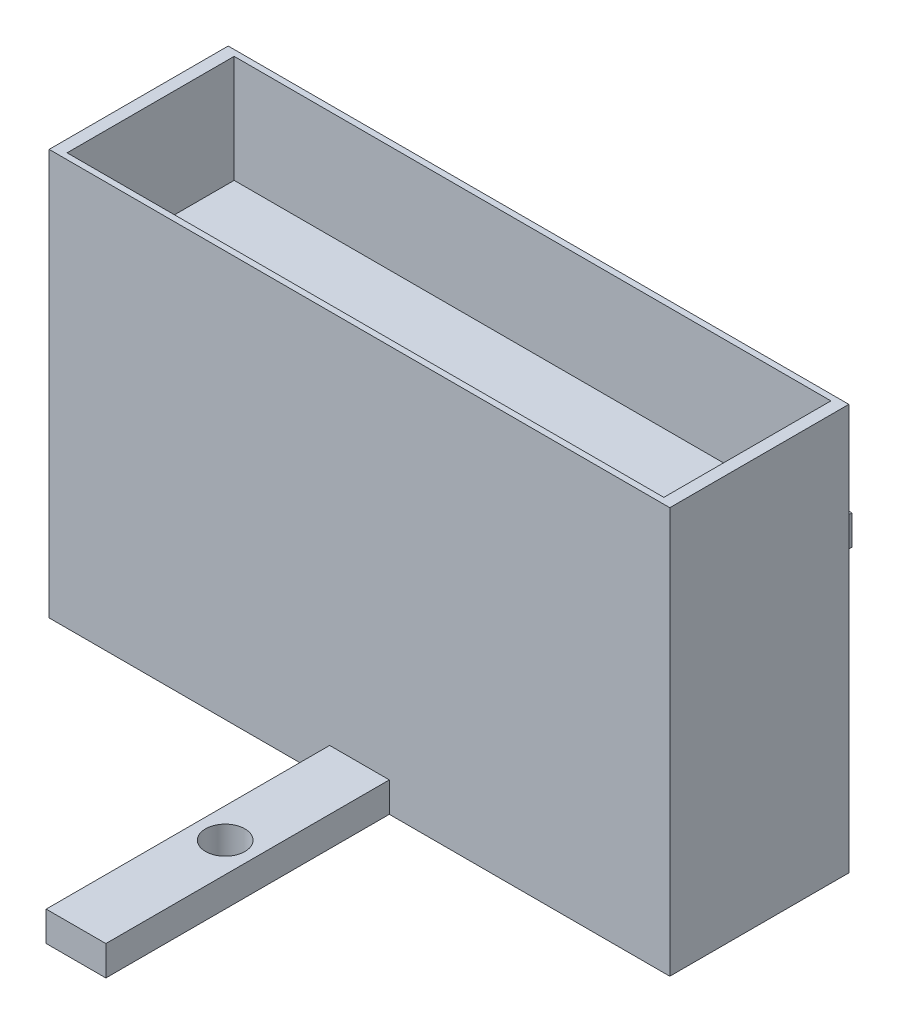
SolidWorks part; units mm, degrees
ref_plane "Front Plane" through (0, 0, 0) normal (0, 0, 1) x (1, 0, 0)
ref_plane "Top Plane" through (0, 0, 0) normal (0, 1, 0) x (1, 0, 0)
ref_plane "Right Plane" through (0, 0, 0) normal (1, 0, 0) x (0, 0, -1)
sketch "Sketch2" plane through (0, 0, 0) normal (0, 1, 0) x (1, 0, 0)
  line L1 (-52, -15) -> (52, -15)
  line L2 (-52, -15) -> (-52, 15)
  line L3 (-52, 15) -> (52, 15)
  line L4 (52, -15) -> (52, 15)
  line L5 (-52, -15) -> (52, 15) construction
  line L6 (-52, 15) -> (52, -15) construction
  point P0 (0, 0)
  point P6 (0, 0)
  point P7 (0, 0)
  point P8 (0, 0)
  point P9 (0, 0)
  point P10 (0, 0)
  point P11 (0, 0)
  point P12 (0, 0)
  point P13 (0, 0)
  point P14 (0, 0)
  point P15 (0, 0)
  point P16 (0, 0)
  point P17 (0, 0)
  point P18 (0, 0)
extrude "Boss-Extrude1" add sketch "Sketch2" along normal blind 68
sketch "Sketch3" plane through (0, 68, 0) normal (0, 1, 0) x (1, 0, 0)
  line L1 (-50, 14) -> (50, 14)
  line L2 (-50, 14) -> (-50, -14)
  line L3 (-50, -14) -> (50, -14)
  line L4 (50, 14) -> (50, -14)
  point P4 (0, 0)
  point P5 (0, 0)
  point P6 (0, 0)
  point P7 (0, 0)
  point P8 (0, 0)
  point P9 (0, 0)
  point P10 (0, 0)
  point P11 (0, 0)
  point P12 (0, 0)
  point P13 (0, 0)
extrude "Cut-Extrude1" cut sketch "Sketch3" against normal blind 18
sketch "Sketch4" plane through (0, 0, 0) normal (0, -1, 0) x (-1, 0, 0)
  line L0 (52, -15) -> (-52, -15) construction
  line L1 (5, -15) -> (-5, -15)
  line L2 (5, -15) -> (5, -62.5)
  line L3 (5, -62.5) -> (-5, -62.5)
  line L4 (-5, -15) -> (-5, -62.5)
extrude "Boss-Extrude3" add sketch "Sketch4" against normal blind 5 separate body
hole_wizard "M6 Clearance Hole1" positions "3DSketch3" profile "Sketch7" hole size "M6" standard "ANSI Metric" end condition through all
sketch3d "3DSketch3"
  point P0 (0, 5, 37.5)
sketch "Sketch7" plane through (0, 5, 37.5) normal (1, 0, 0) x (0, 0, 1)
  line L0 (0, 0) -> (0, 5)
  line L1 (0, 5) -> (3.3, 5)
  line L2 (3.3, 5) -> (3.3, 0)
  line L5 (3.3, 0) -> (0, 0)
  line L11 (0, -6.35) -> (0, 107.95) construction
  dimension "Thru Hole Dia." = 6.6
  dimension "Thru Hole Depth" = 5
sketch "Sketch13" plane through (0, 0, 0) normal (0, -1, 0) x (-1, 0, 0)
  line L0 (-52, 15) -> (52, 15) construction
  line L1 (5, 15) -> (-5, 15)
  line L2 (5, 15) -> (5, 62.5)
  line L3 (5, 62.5) -> (-5, 62.5)
  line L4 (-5, 15) -> (-5, 62.5)
extrude "Boss-Extrude4" add sketch "Sketch13" against normal blind 5 separate body
hole_wizard "M6 Clearance Hole2" positions "3DSketch4" profile "Sketch14" hole size "M6" standard "ANSI Metric" end condition through all
sketch3d "3DSketch4"
  point P0 (0, 5, -37.5)
sketch "Sketch14" plane through (0, 5, -37.5) normal (1, 0, 0) x (0, 0, 1)
  line L0 (0, 0) -> (0, 5)
  line L1 (0, 5) -> (3.3, 5)
  line L2 (3.3, 5) -> (3.3, 0)
  line L5 (3.3, 0) -> (0, 0)
  line L11 (0, -6.35) -> (0, 107.95) construction
  dimension "Thru Hole Dia." = 6.6
  dimension "Thru Hole Depth" = 5
